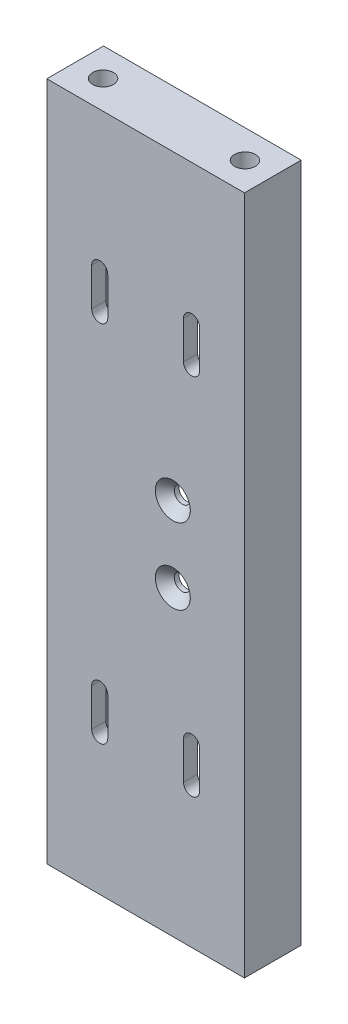
SolidWorks part; units mm, degrees
ref_plane "Front Plane" through (0, 0, 0) normal (0, 0, 1) x (1, 0, 0)
ref_plane "Top Plane" through (0, 0, 0) normal (0, 1, 0) x (1, 0, 0)
ref_plane "Right Plane" through (0, 0, 0) normal (1, 0, 0) x (0, 0, -1)
sketch "Sketch1" plane through (0, 0, 0) normal (0, 0, 1) x (1, 0, 0)
  line L1 (-20.9, 0) -> (20.9, 0)
  line L2 (-20.9, 0) -> (-20.9, 143.8)
  line L3 (-20.9, 143.8) -> (20.9, 143.8)
  line L4 (20.9, 0) -> (20.9, 143.8)
  point P4 (0, 0)
  dimension "D1" = 143.8
  dimension "D2" = 41.8
extrude "Boss-Extrude1" add sketch "Sketch1" against normal blind 12
shell "Shell1" thickness 7
sketch "Sketch2" plane through (0, 143.8, 0) normal (0, 1, 0) x (1, 0, 0)
  line L0 (0, 12) -> (0, 0) construction
  line L1 (20.9, 12) -> (-20.9, 12) construction
  line L5 (20.9, 0) -> (-20.9, 0) construction
  circle A1 centre (-15, 6) radius 2.2
  circle A2 centre (15, 6) radius 2.2
  dimension "D1" = 4.4
  dimension "D2" = 6
  dimension "D3" = 15
extrude "Cut-Extrude1" cut sketch "Sketch2" against normal blind 5.2
ref_plane "Plane1" through (0, 71.9, 0) normal (0, 1, 0) x (1, 0, 0)
mirror "Mirror1" about plane through (0, 71.9, 0) normal (0, 1, 0) of "Cut-Extrude1"
sketch "Sketch3" plane through (-20.9, 0, 0) normal (-1, 0, 0) x (0, 0, 1)
  line L0 (-6, 143.8) -> (-6, 0) construction
  line L1 (-12, 143.8) -> (0, 143.8) construction
  line L2 (-12, 0) -> (0, 0) construction
  line L3 (0, 71.9) -> (-12, 71.9) construction
  line L4 (0, 143.8) -> (0, 0) construction
  line L5 (-12, 143.8) -> (-12, 0) construction
  circle A0 centre (-6, 129.4) radius 2.2
  circle A1 centre (-6, 14.4) radius 2.2
  dimension "D1" = 57.5
  dimension "D2" = 4.4
extrude "Cut-Extrude2" cut sketch "Sketch3" against normal blind 5.2
sketch "Sketch5" plane through (0, 0, -3) normal (0, 0, -1) x (-1, 0, 0)
  line L0 (-13.9, 71.9) -> (13.9, 71.9) construction
  line L1 (-13.9, 7) -> (-13.9, 136.8) construction
  line L2 (13.9, 136.8) -> (13.9, 7) construction
  line L3 (-5.75, 63.9) -> (-5.75, 79.9) construction
  line L4 (8, 61.65) -> (-8, 61.65) construction
  line L5 (8, 61.65) -> (8, 82.15) construction
  line L6 (8, 82.15) -> (-8, 82.15) construction
  line L7 (-8, 61.65) -> (-8, 82.15) construction
  line L8 (8, 61.65) -> (-8, 82.15) construction
  line L9 (8, 82.15) -> (-8, 61.65) construction
  circle A0 centre (-5.75, 63.9) radius 1.7
  circle A1 centre (-5.75, 79.9) radius 1.7
  point P6 (0, 71.9)
  point P15 (-5.75, 71.9)
  dimension "D2" = 3.4
  dimension "D1" = 16
  dimension "D3" = 16
  dimension "D4" = 20.5
  dimension "D5" = 2.25
extrude "Cut-Extrude3" cut sketch "Sketch5" against normal blind 10
chamfer "Chamfer1" distance 2 angle 45 2 edges at (4.05, 63.9, 0) (4.05, 79.9, 0)
sketch "Sketch6" plane through (0, 0, -3) normal (0, 0, -1) x (-1, 0, 0)
  line L0 (9.7096, 37.4) -> (9.7096, 29.4) construction
  line L1 (0, -17.1921) -> (0, 151.7701) construction
  line L2 (11.4096, 37.4) -> (11.4096, 29.4)
  line L3 (8.0096, 37.4) -> (8.0096, 29.4)
  line L4 (-0.2154, 71.9) -> (46.3348, 71.9) construction
  line L5 (9.7096, 106.4) -> (9.7096, 114.4) construction
  line L6 (11.4096, 106.4) -> (11.4096, 114.4)
  line L7 (8.0096, 106.4) -> (8.0096, 114.4)
  line L8 (0.2154, 71.9) -> (-46.3348, 71.9) construction
  line L9 (-9.7096, 106.4) -> (-9.7096, 114.4) construction
  line L10 (-11.4096, 106.4) -> (-11.4096, 114.4)
  line L11 (-8.0096, 106.4) -> (-8.0096, 114.4)
  line L12 (-9.7096, 37.4) -> (-9.7096, 29.4) construction
  line L13 (-11.4096, 37.4) -> (-11.4096, 29.4)
  line L14 (-8.0096, 37.4) -> (-8.0096, 29.4)
  arc A0 (11.4096, 37.4) -> (8.0096, 37.4) centre (9.7096, 37.4) ccw
  arc A1 (8.0096, 29.4) -> (11.4096, 29.4) centre (9.7096, 29.4) ccw
  arc A2 (11.4096, 106.4) -> (8.0096, 106.4) centre (9.7096, 106.4) cw
  arc A3 (8.0096, 114.4) -> (11.4096, 114.4) centre (9.7096, 114.4) cw
  arc A4 (-11.4096, 106.4) -> (-8.0096, 106.4) centre (-9.7096, 106.4) ccw
  arc A5 (-8.0096, 114.4) -> (-11.4096, 114.4) centre (-9.7096, 114.4) ccw
  arc A6 (-11.4096, 37.4) -> (-8.0096, 37.4) centre (-9.7096, 37.4) cw
  arc A7 (-8.0096, 29.4) -> (-11.4096, 29.4) centre (-9.7096, 29.4) cw
  point P5 (9.7096, 33.4)
  point P16 (9.7096, 110.4)
  point P25 (-9.7096, 110.4)
  point P32 (-9.7096, 33.4)
  dimension "D2" = 1.7
  dimension "D1" = 8
extrude "Cut-Extrude4" cut sketch "Sketch6" against normal blind 3.5
